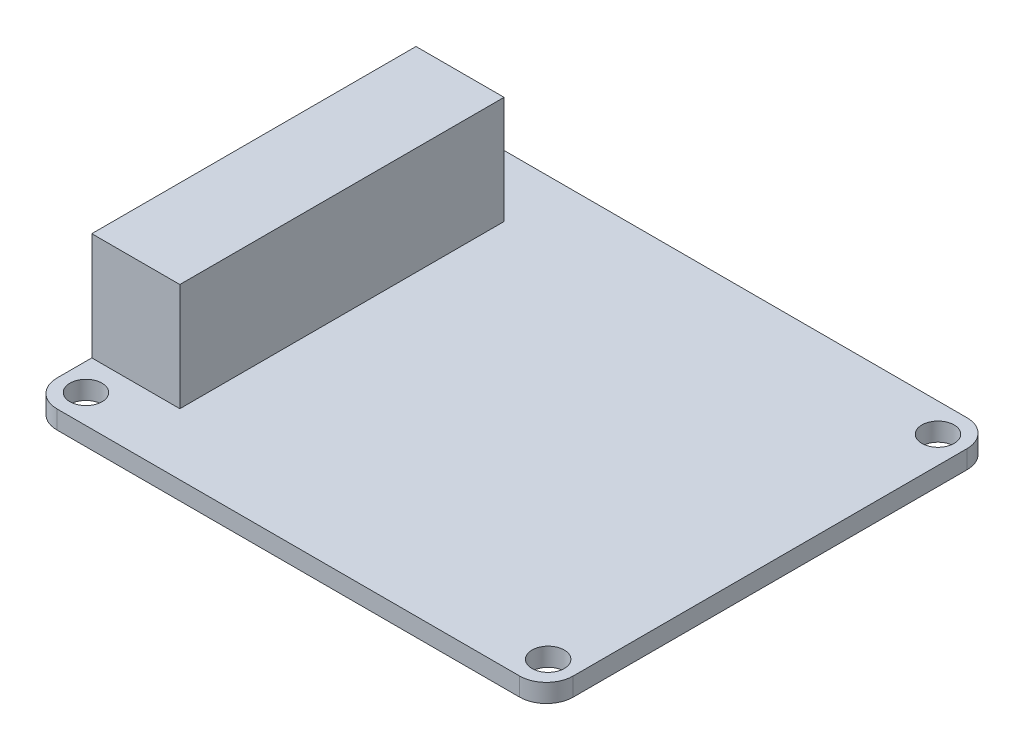
SolidWorks part; units mm, degrees
ref_plane "Front Plane" through (0, 0, 0) normal (0, 0, 1) x (1, 0, 0)
ref_plane "Top Plane" through (0, 0, 0) normal (0, 1, 0) x (1, 0, 0)
ref_plane "Right Plane" through (0, 0, 0) normal (1, 0, 0) x (0, 0, -1)
sketch "Sketch2" plane through (0, 0, 0) normal (0, 1, 0) x (1, 0, 0)
  line L1 (-24.065, -20.855) -> (24.065, -20.855)
  line L2 (-24.065, -20.855) -> (-24.065, 20.855)
  line L3 (-24.065, 20.855) -> (24.065, 20.855)
  line L4 (24.065, -20.855) -> (24.065, 20.855)
  line L5 (-24.065, -20.855) -> (24.065, 20.855) construction
  line L6 (-24.065, 20.855) -> (24.065, -20.855) construction
  point P0 (0, 0)
  dimension "D1" = 48.13
  dimension "D2" = 41.71
extrude "Boss-Extrude1" add sketch "Sketch2" along normal blind 1.71
sketch "Sketch3" plane through (0, 1.71, 0) normal (0, 1, 0) x (1, 0, 0)
  line L0 (-23.065, 20.855) -> (-23.065, 19.675) construction
  line L1 (24.065, 20.855) -> (-24.065, 20.855) construction
  line L2 (-24.065, 18.1515) -> (-23.065, 18.1515) construction
  line L3 (-24.065, 20.855) -> (-24.065, -20.855) construction
  line L4 (-23.065, 19.675) -> (-23.065, 16.9757) construction
  line L5 (-21.5457, 18.1743) -> (-21.5457, -20.855) construction
  line L6 (-24.065, -20.855) -> (24.065, -20.855) construction
  line L7 (-21.5457, -20.855) -> (-21.5457, -18.175)
  circle A0 centre (-21.5457, 18.1743) radius 1.5
  circle A1 centre (-21.5457, -18.175) radius 1.5
  dimension "D3" = 2.6807
  dimension "D1" = 1
  dimension "D2" = 1.18
  dimension "D4" = 2.5193
extrude "Cut-Extrude1" cut sketch "Sketch3" against normal blind 10.71 contours A0
sketch "Sketch4" plane through (0, 1.71, 0) normal (0, 1, 0) x (1, 0, 0)
  line L0 (-21.5457, 18.1743) -> (-21.5457, -20.855) construction
  line L1 (-24.065, -20.855) -> (24.065, -20.855) construction
  line L2 (-21.5457, -20.855) -> (-21.5457, -18.175)
  circle A0 centre (-21.5457, -18.175) radius 1.5
  dimension "D1" = 2.68
extrude "Cut-Extrude2" cut sketch "Sketch4" against normal blind 10.71 contours L0 A0 L2 | A0 L0 L2
fillet "Fillet3" radius 2.5 4 edges at (24.065, 0.855, -20.855) (-24.065, 0.855, -20.855) (-24.065, 0.855, 20.855) (24.065, 0.855, 20.855)
ref_plane "Plane1" through (0, 0, 0) normal (1, 0, 0) x (0, 0, -1)
mirror "Mirror1" about plane through (0, 0, 0) normal (1, 0, 0) of "Cut-Extrude2", "Cut-Extrude1"
sketch "Sketch8" plane through (0, 1.71, 0) normal (0, 1, 0) x (1, 0, 0)
  line L0 (-15.855, 20.855) -> (-15.855, 15.115) construction
  line L1 (21.565, 20.855) -> (-21.565, 20.855) construction
  line L2 (-15.855, 15.115) -> (-15.855, -20.855) construction
  line L3 (-21.565, -20.855) -> (21.565, -20.855) construction
  line L4 (-15.855, -20.855) -> (-15.855, -15.115) construction
  line L5 (-24.065, 18.355) -> (-24.065, -18.355) construction
  line L7 (-15.855, -15.115) -> (-24.065, -15.115)
  line L8 (-15.855, -15.115) -> (-15.855, 15.115)
  line L9 (-15.855, 15.115) -> (-24.065, 15.115)
  line L10 (-24.065, -15.115) -> (-24.065, 15.115)
  dimension "D1" = 8.21
extrude "Boss-Extrude2" add sketch "Sketch8" along normal blind 10.03
